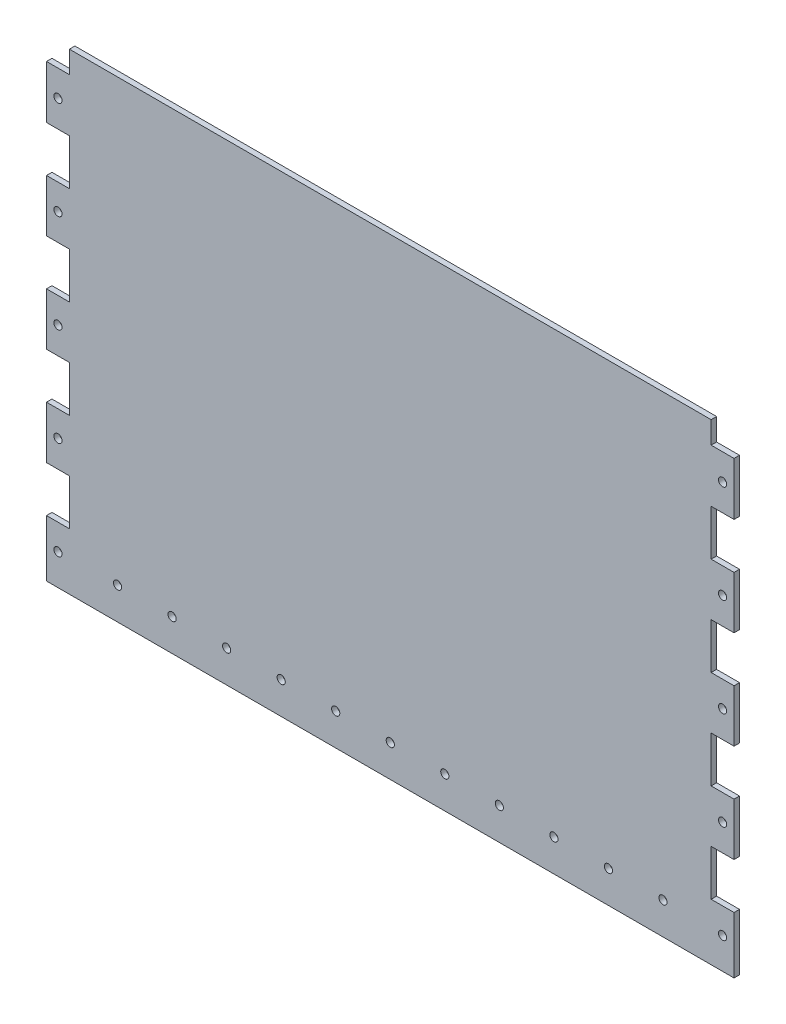
SolidWorks part; units mm, degrees
material "FR4"
ref_plane "前视基准面" through (0, 0, 0) normal (0, 0, 1) x (1, 0, 0)
ref_plane "上视基准面" through (0, 0, 0) normal (0, 1, 0) x (1, 0, 0)
ref_plane "右视基准面" through (0, 0, 0) normal (1, 0, 0) x (0, 0, -1)
sketch "草图1" plane through (0, 0, 0) normal (0, 0, 1) x (1, 0, 0)
  line L1 (126.05, -83.1) -> (-126.05, -83.1)
  line L2 (126.05, -83.1) -> (126.05, 83.1)
  line L3 (126.05, 83.1) -> (-126.05, 83.1)
  line L4 (-126.05, -83.1) -> (-126.05, 83.1)
  line L5 (126.05, -83.1) -> (-126.05, 83.1) construction
  line L6 (126.05, 83.1) -> (-126.05, -83.1) construction
  point P0 (0, 0)
  dimension "D1" = 252.1
  dimension "D2" = 166.2
extrude "凸台-拉伸1" add sketch "草图1" along normal mid plane 2
sketch "草图2" plane through (0, 0, 1) normal (0, 0, 1) x (1, 0, 0)
  line L5 (0, 0) -> (144.4976, 0) construction
  line L6 (0, 0) -> (0, 93.1697) construction
  line L20 (-126.05, 83.1) -> (-126.05, -83.1) construction
  line L21 (-126.05, 63.5) -> (-117.65, 63.5)
  line L23 (-126.05, 63.5) -> (-126.05, 46.7)
  line L28 (-126.05, 46.7) -> (-117.65, 46.7)
  line L29 (-117.65, 63.5) -> (-117.65, 46.7)
  line L30 (126.05, 83.1) -> (-126.05, 83.1) construction
  line L40 (-126.05, 27.5) -> (-117.65, 27.5)
  line L41 (-126.05, 27.5) -> (-126.05, 10.7)
  line L42 (-126.05, 10.7) -> (-117.65, 10.7)
  line L43 (-117.65, 27.5) -> (-117.65, 10.7)
  line L44 (-126.05, -8.5) -> (-117.65, -8.5)
  line L45 (-126.05, -8.5) -> (-126.05, -25.3)
  line L46 (-126.05, -25.3) -> (-117.65, -25.3)
  line L47 (-117.65, -8.5) -> (-117.65, -25.3)
  line L48 (-126.05, -44.5) -> (-117.65, -44.5)
  line L49 (-126.05, -44.5) -> (-126.05, -61.3)
  line L50 (-126.05, -61.3) -> (-117.65, -61.3)
  line L51 (-117.65, -44.5) -> (-117.65, -61.3)
  line L52 (-126.05, 63.5) -> (-126.05, 27.5) construction
  line L53 (126.05, 63.5) -> (126.05, 27.5) construction
  line L54 (117.65, -44.5) -> (117.65, -61.3)
  line L55 (126.05, -61.3) -> (117.65, -61.3)
  line L56 (126.05, -44.5) -> (126.05, -61.3)
  line L57 (126.05, -44.5) -> (117.65, -44.5)
  line L58 (117.65, -8.5) -> (117.65, -25.3)
  line L59 (126.05, -25.3) -> (117.65, -25.3)
  line L60 (126.05, -8.5) -> (126.05, -25.3)
  line L61 (126.05, -8.5) -> (117.65, -8.5)
  line L62 (117.65, 27.5) -> (117.65, 10.7)
  line L63 (126.05, 10.7) -> (117.65, 10.7)
  line L64 (126.05, 27.5) -> (126.05, 10.7)
  line L65 (126.05, 27.5) -> (117.65, 27.5)
  line L66 (117.65, 63.5) -> (117.65, 46.7)
  line L67 (126.05, 46.7) -> (117.65, 46.7)
  line L68 (126.05, 63.5) -> (126.05, 46.7)
  line L69 (126.05, 63.5) -> (117.65, 63.5)
  line L70 (-121.85, 83.1) -> (-121.85, 63.5) construction
  line L71 (-121.85, 73.3) -> (-121.85, 37.3) construction
  line L72 (126.05, 77.9) -> (126.05, 86.1634) construction
  line L73 (-126.05, 83.1) -> (126.05, 83.1)
  line L74 (-126.05, 83.1) -> (-126.05, 82.9)
  line L75 (-126.05, 82.9) -> (126.05, 82.9)
  line L76 (126.05, 83.1) -> (126.05, 82.9)
  line L77 (126.05, -83.1) -> (126.05, 83.1) construction
  line L78 (-126.05, -83.1) -> (126.05, -83.1)
  line L79 (-126.05, -83.1) -> (-126.05, -82.1)
  line L80 (-126.05, -82.1) -> (126.05, -82.1)
  line L81 (126.05, -83.1) -> (126.05, -82.1)
  circle A0 centre (-121.85, 73.3) radius 1.5
  circle A1 centre (-121.85, 37.3) radius 1.5
  circle A2 centre (-121.85, 1.3) radius 1.5
  circle A3 centre (-121.85, -34.7) radius 1.5
  circle A4 centre (-121.85, -70.7) radius 1.5
  circle A5 centre (121.85, -70.7) radius 1.5
  circle A6 centre (121.85, -34.7) radius 1.5
  circle A7 centre (121.85, 1.3) radius 1.5
  circle A8 centre (121.85, 37.3) radius 1.5
  circle A9 centre (121.85, 73.3) radius 1.5
  dimension "D4" = 4
  dimension "D6" = 3
  dimension "D1" = 8.4
  dimension "D2" = 19.6
  dimension "D3" = 16.8
  dimension "D5" = 36
  dimension "D8" = 36
  dimension "D9" = 0.2
  dimension "D10" = 1
  dimension "D7" = 5
extrude "Cut-Extrude1" cut sketch "草图2" against normal blind 10
sketch "Sketch1" plane through (0, 0, 1) normal (0, 0, 1) x (1, 0, 0)
  circle A0 centre (100, -70.35) radius 1.5 construction
  circle A1 centre (80, -70.35) radius 1.5 construction
  circle A2 centre (60, -70.35) radius 1.5 construction
  circle A3 centre (40, -70.35) radius 1.5 construction
  circle A4 centre (20, -70.35) radius 1.5 construction
  circle A5 centre (0, -70.35) radius 1.5 construction
  circle A6 centre (-20, -70.35) radius 1.5 construction
  circle A7 centre (-40, -70.35) radius 1.5 construction
  circle A8 centre (-60, -70.35) radius 1.5 construction
  circle A9 centre (-80, -70.35) radius 1.5 construction
  circle A10 centre (-100, -70.35) radius 1.5 construction
  circle A11 centre (100, -70.35) radius 1.5
  circle A12 centre (80, -70.35) radius 1.5
  circle A13 centre (60, -70.35) radius 1.5
  circle A14 centre (40, -70.35) radius 1.5
  circle A15 centre (20, -70.35) radius 1.5
  circle A16 centre (0, -70.35) radius 1.5
  circle A17 centre (-20, -70.35) radius 1.5
  circle A18 centre (-40, -70.35) radius 1.5
  circle A19 centre (-60, -70.35) radius 1.5
  circle A20 centre (-80, -70.35) radius 1.5
  circle A21 centre (-100, -70.35) radius 1.5
extrude "Cut-Extrude2" cut sketch "Sketch1" against normal blind 10
sketch "Sketch2" plane through (0, 0, 1) normal (0, 0, 1) x (1, 0, 0)
  line L1 (-117.65, 82.9) -> (117.65, 82.9)
  line L2 (-117.65, 82.9) -> (-117.65, 91)
  line L3 (-117.65, 91) -> (117.65, 91)
  line L4 (117.65, 82.9) -> (117.65, 91)
  line L6 (118.05, 91.4) -> (118.05, 83.1) construction
  line L7 (-118.05, 91.4) -> (-118.05, 83.1) construction
  line L8 (140.24, 91.4) -> (-126.05, 91.4) construction
  line L9 (-126.05, 82.9) -> (126.05, 82.9) construction
  dimension "D1" = 0.4
  dimension "D2" = 0.4
  dimension "D3" = 0.4
extrude "Boss-Extrude1" add sketch "Sketch2" against normal blind 2
